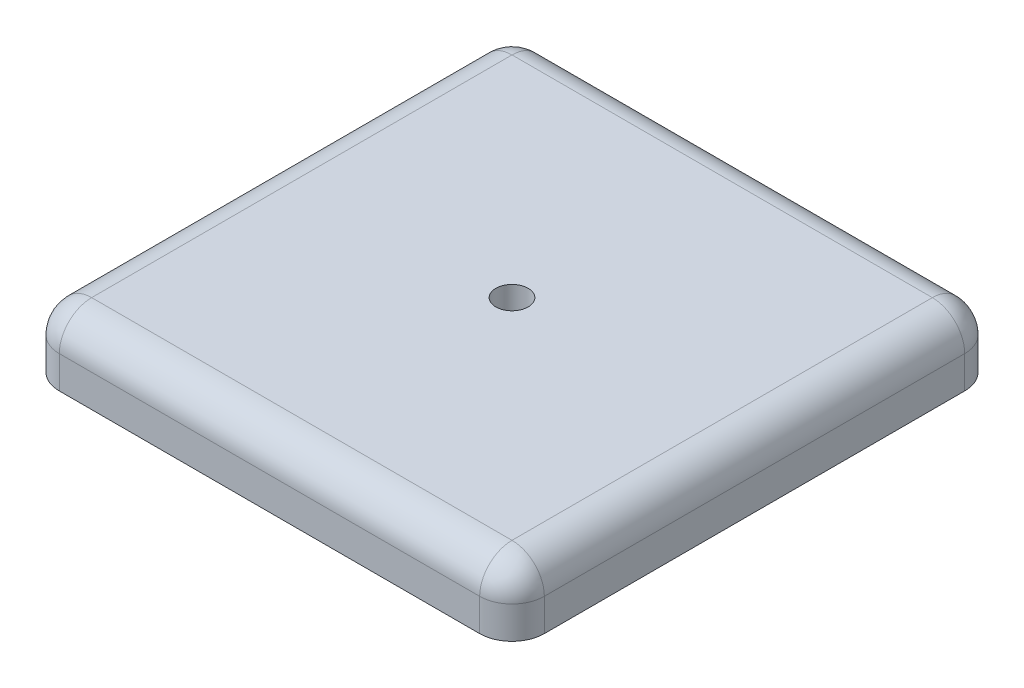
SolidWorks part; units mm, degrees
ref_plane "Front Plane" through (0, 0, 0) normal (0, 0, 1) x (1, 0, 0)
ref_plane "Top Plane" through (0, 0, 0) normal (0, 1, 0) x (1, 0, 0)
ref_plane "Right Plane" through (0, 0, 0) normal (1, 0, 0) x (0, 0, -1)
sketch "Sketch1" plane through (0, 0, 0) normal (0, 1, 0) x (1, 0, 0)
  line L1 (0, 0) -> (300, 0)
  line L2 (0, 0) -> (0, 300)
  line L3 (0, 300) -> (300, 300)
  line L4 (300, 0) -> (300, 300)
  dimension "D1" = 300
  dimension "D2" = 300
extrude "Boss-Extrude1" add sketch "Sketch1" along normal blind 40
fillet "Fillet1" radius 20 8 edges at (150, 40, -300) (300, 40, -150) (150, 40, 0) (0, 40, -150) (300, 20, 0) (0, 20, 0) (300, 20, -300) (0, 20, -300)
sketch "Sketch2" plane through (0, 0, 0) normal (0, -1, 0) x (1, 0, 0)
  line L0 (20, 0) -> (280, 0) construction
  line L1 (274.5, -25.5) -> (25.5, -25.5)
  line L2 (274.5, -25.5) -> (274.5, -274.5)
  line L3 (274.5, -274.5) -> (25.5, -274.5)
  line L4 (25.5, -25.5) -> (25.5, -274.5)
  line L5 (300, -20) -> (300, -280) construction
  line L6 (0, -280) -> (0, -20) construction
  line L7 (280, -300) -> (20, -300) construction
  dimension "D1" = 25.5
  dimension "D2" = 25.5
  dimension "D3" = 25.5
  dimension "D4" = 25.5
extrude "Boss-Extrude2" add sketch "Sketch2" along normal blind 15
sketch "Sketch3" plane through (0, -15, 0) normal (0, -1, 0) x (1, 0, 0)
  line L0 (274.5, -25.5) -> (25.5, -25.5) construction
  line L1 (80, -60) -> (220, -60)
  line L2 (80, -60) -> (80, -120)
  line L3 (80, -120) -> (220, -120)
  line L4 (220, -60) -> (220, -120)
  line L5 (80, -180) -> (220, -180)
  line L6 (80, -180) -> (80, -240)
  line L7 (80, -240) -> (220, -240)
  line L8 (220, -180) -> (220, -240)
  line L9 (25.5, -25.5) -> (25.5, -274.5) construction
  dimension "D1" = 60
  dimension "D2" = 60
  dimension "D3" = 140
  dimension "D4" = 60
  dimension "D5" = 34.5
  dimension "D6" = 54.5
extrude "Cut-Extrude1" cut sketch "Sketch3" against normal blind 25
sketch "Sketch4" plane through (0, -15, 0) normal (0, -1, 0) x (-1, 0, 0)
  line L0 (0, 280) -> (0, 20) construction
  line L1 (-20, 0) -> (-280, 0) construction
  circle A0 centre (-150, 150) radius 10
  dimension "D3" = 20
  dimension "D1" = 150
  dimension "D2" = 150
extrude "Cut-Extrude2" cut sketch "Sketch4" against normal through all
